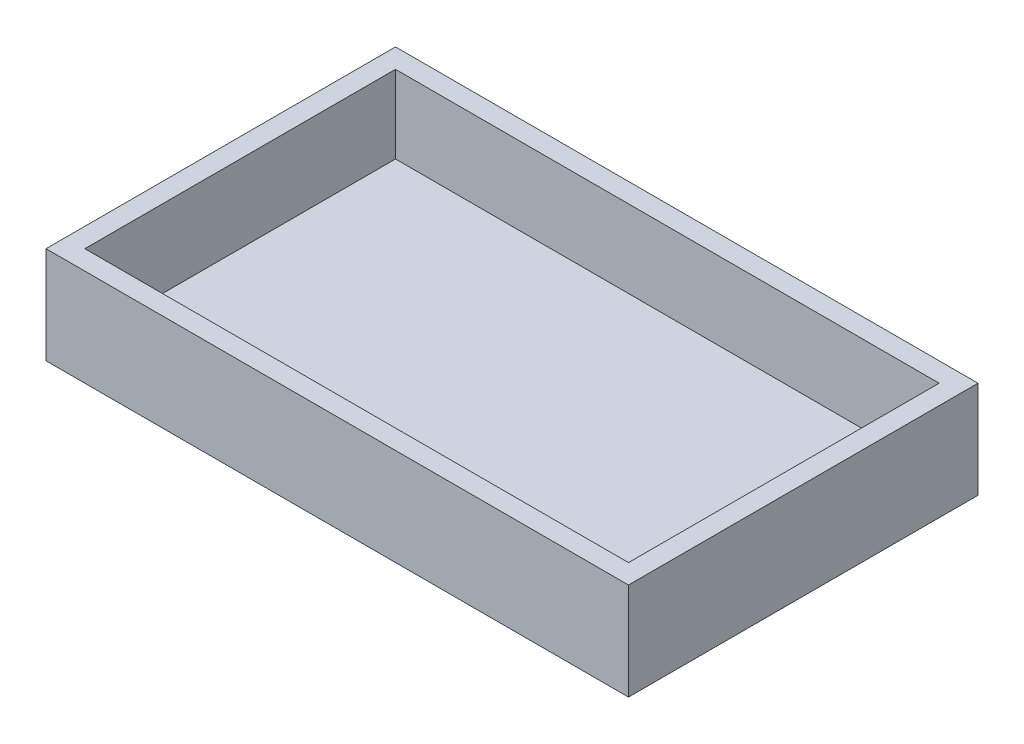
SolidWorks part; units mm, degrees
ref_plane "Front Plane" through (0, 0, 0) normal (0, 0, 1) x (1, 0, 0)
ref_plane "Top Plane" through (0, 0, 0) normal (0, 1, 0) x (1, 0, 0)
ref_plane "Right Plane" through (0, 0, 0) normal (1, 0, 0) x (0, 0, -1)
sketch "Sketch1" plane through (0, 0, 0) normal (0, 1, 0) x (1, 0, 0)
  line L1 (150, -90) -> (-150, -90)
  line L2 (150, -90) -> (150, 90)
  line L3 (150, 90) -> (-150, 90)
  line L4 (-150, -90) -> (-150, 90)
  line L5 (150, -90) -> (-150, 90) construction
  line L6 (150, 90) -> (-150, -90) construction
  point P0 (0, 0)
  dimension "D1" = 300
  dimension "D2" = 180
extrude "Boss-Extrude1" add sketch "Sketch1" along normal blind 50
sketch "Sketch2" plane through (0, 50, 0) normal (0, 1, 0) x (1, 0, 0)
  line L0 (150, 90) -> (-150, 90) construction
  line L1 (-140, 80) -> (140, 80)
  line L2 (-140, 80) -> (-140, -80)
  line L3 (-140, -80) -> (140, -80)
  line L4 (140, 80) -> (140, -80)
  line L5 (-150, 90) -> (-150, -90) construction
  line L6 (150, -90) -> (150, 90) construction
  line L7 (-150, -90) -> (150, -90) construction
  dimension "D1" = 10
  dimension "D2" = 10
  dimension "D3" = 10
  dimension "D4" = 10
extrude "Cut-Extrude1" cut sketch "Sketch2" against normal blind 40
